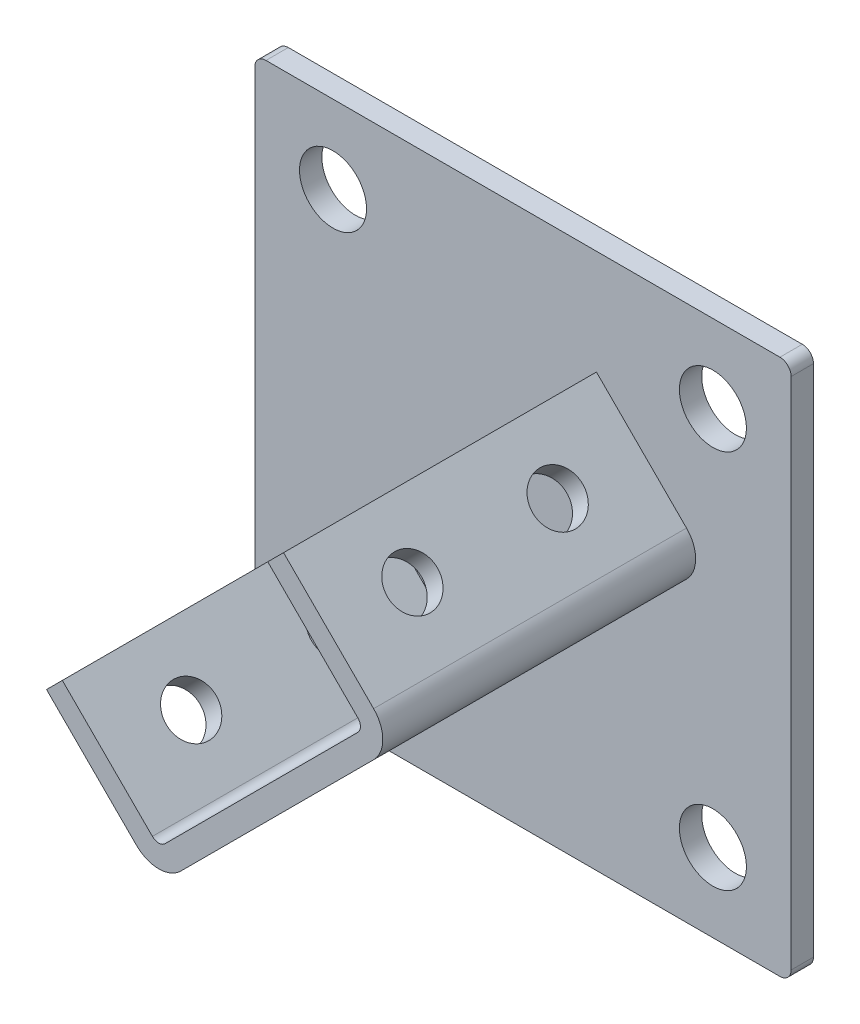
SolidWorks part; units mm, degrees
ref_plane "Front Plane" through (0, 0, 0) normal (0, 0, 1) x (1, 0, 0)
ref_plane "Top Plane" through (0, 0, 0) normal (0, 1, 0) x (1, 0, 0)
ref_plane "Right Plane" through (0, 0, 0) normal (1, 0, 0) x (0, 0, -1)
sketch "Sketch1" plane through (0, 0, 0) normal (0, 0, 1) x (1, 0, 0)
  line L0 (-76.2, -76.2) -> (76.2, 76.2) construction
  line L1 (-73.025, 76.2) -> (73.025, 76.2)
  line L2 (-76.2, 73.025) -> (-76.2, -73.025)
  line L3 (-73.025, -76.2) -> (73.025, -76.2)
  line L4 (76.2, 73.025) -> (76.2, -73.025)
  line L5 (-53.975, 53.975) -> (-53.975, -53.975) construction
  line L6 (-53.975, -53.975) -> (53.975, -53.975) construction
  line L7 (53.975, -53.975) -> (53.975, 53.975) construction
  line L8 (53.975, 53.975) -> (-53.975, 53.975) construction
  line L9 (-53.975, 53.975) -> (53.975, -53.975) construction
  circle A0 centre (-53.975, 53.975) radius 9.525
  circle A1 centre (-53.975, -53.975) radius 9.525
  arc A2 (76.2, 73.025) -> (73.025, 76.2) centre (73.025, 73.025) ccw
  arc A3 (-76.2, -73.025) -> (-73.025, -76.2) centre (-73.025, -73.025) ccw
  arc A4 (73.025, -76.2) -> (76.2, -73.025) centre (73.025, -73.025) ccw
  arc A5 (-73.025, 76.2) -> (-76.2, 73.025) centre (-73.025, 73.025) ccw
  circle A6 centre (53.975, 53.975) radius 9.525
  circle A7 centre (53.975, -53.975) radius 9.525
  point P19 (-76.2, 76.2)
  dimension "D3" = 19.05
  dimension "D6" = 3.175
  dimension "D1" = 152.4
  dimension "D2" = 152.4
  dimension "D4" = 107.95
extrude "Boss-Extrude1" add sketch "Sketch1" along normal blind 6.35
sketch "Sketch2" plane through (0, 0, 6.35) normal (0, 0, 1) x (1, 0, 0)
  line L0 (-58.3717, 0) -> (58.3717, 0) construction
  line L1 (-41.9827, -16.389) -> (-16.389, -41.9827)
  line L2 (-41.9827, -12.7969) -> (12.7969, 41.9827) construction
  line L3 (-12.7969, -41.9827) -> (41.9827, 12.7969)
  line L4 (16.389, 41.9827) -> (41.9827, 16.389)
  line L6 (40.1866, 14.5929) -> (-40.1866, -14.5929) construction
  line L7 (0, 0) -> (-29.1858, -29.1858) construction
  arc A0 (41.9827, 12.7969) -> (41.9827, 16.389) centre (40.1866, 14.5929) ccw
  arc A1 (12.7969, 41.9827) -> (16.389, 41.9827) centre (14.5929, 40.1866) cw construction
  arc A2 (-41.9827, -12.7969) -> (-41.9827, -16.389) centre (-40.1866, -14.5929) ccw construction
  arc A3 (-16.389, -41.9827) -> (-12.7969, -41.9827) centre (-14.5929, -40.1866) ccw
  dimension "D2" = 41.275
  dimension "D3" = 82.55
  dimension "D1" = 2.54
  dimension "D4" = 45
extrude "Extrude-Thin1" add sketch "Sketch2" along normal blind 88.9 thin
sketch "Sketch4" plane through (0, 0, 0) normal (1, 0, 0) x (0, 0, -1)
  line L0 (0, 0) -> (-45.4657, 0) construction
ref_plane "Plane1" through (0, 0, 0) normal (0.7071, -0.7071, 0) x (0, 0, 1)
sketch "Sketch3" plane through (0, 0, 0) normal (0.7071, -0.7071, 0) x (-0.7071, -0.7071, 0)
  line L0 (-38.735, -95.25) -> (-38.735, -6.35) construction
  line L1 (0, 0) -> (0, -45.4657) construction
  line L2 (0, -6.35) -> (0, -45.4657) construction
  line L3 (-20.6375, -30.1625) -> (-20.6375, -71.4375) construction
  line L4 (-20.6375, -50.8) -> (-38.735, -50.8) construction
  line L6 (-38.735, -6.35) -> (38.735, -6.35) construction
  circle A0 centre (-20.6375, -30.1625) radius 7.112
  circle A1 centre (-20.6375, -71.4375) radius 7.112
  circle A2 centre (20.6375, -71.4375) radius 7.112
  circle A3 centre (20.6375, -30.1625) radius 7.112
  dimension "D3" = 14.224
  dimension "D1" = 41.275
  dimension "D2" = 20.6375
extrude "Cut-Extrude1" cut sketch "Sketch3" along normal through all
ref_axis "Axis1" through (14.5929, 14.5929, 71.4375) along (0, 0, -1)
pattern_circular "CirPattern1" count 4 over 360 about axis through (14.5929, 14.5929, 71.4375) along (0, 0, -1) skipping 2 of "Cut-Extrude1"
sketch "Sketch5" plane through (0, 0, 6.35) normal (0, 0, 1) x (1, 0, 0)
  line L4 (76.2, -73.025) -> (76.2, 73.025)
  line L5 (-73.025, -76.2) -> (73.025, -76.2)
  line L6 (-76.2, 73.025) -> (-76.2, -73.025)
  line L7 (73.025, 76.2) -> (-73.025, 76.2)
  line L8 (76.2, -73.025) -> (76.2, 73.025)
  line L9 (-73.025, -76.2) -> (73.025, -76.2)
  line L10 (-76.2, 73.025) -> (-76.2, -73.025)
  line L11 (73.025, 76.2) -> (-73.025, 76.2)
  arc A4 (76.2, 73.025) -> (73.025, 76.2) centre (73.025, 73.025) ccw
  arc A5 (73.025, -76.2) -> (76.2, -73.025) centre (73.025, -73.025) ccw
  arc A6 (-76.2, -73.025) -> (-73.025, -76.2) centre (-73.025, -73.025) ccw
  arc A7 (-73.025, 76.2) -> (-76.2, 73.025) centre (-73.025, 73.025) ccw
  arc A8 (76.2, 73.025) -> (73.025, 76.2) centre (73.025, 73.025) ccw
  arc A9 (73.025, -76.2) -> (76.2, -73.025) centre (73.025, -73.025) ccw
  arc A10 (-76.2, -73.025) -> (-73.025, -76.2) centre (-73.025, -73.025) ccw
  arc A11 (-73.025, 76.2) -> (-76.2, 73.025) centre (-73.025, 73.025) ccw
  dimension "D1" = 0
extrude "Boss-Extrude2" [suppressed] add sketch "Sketch5" against normal up to surface (6.35 mm away)
